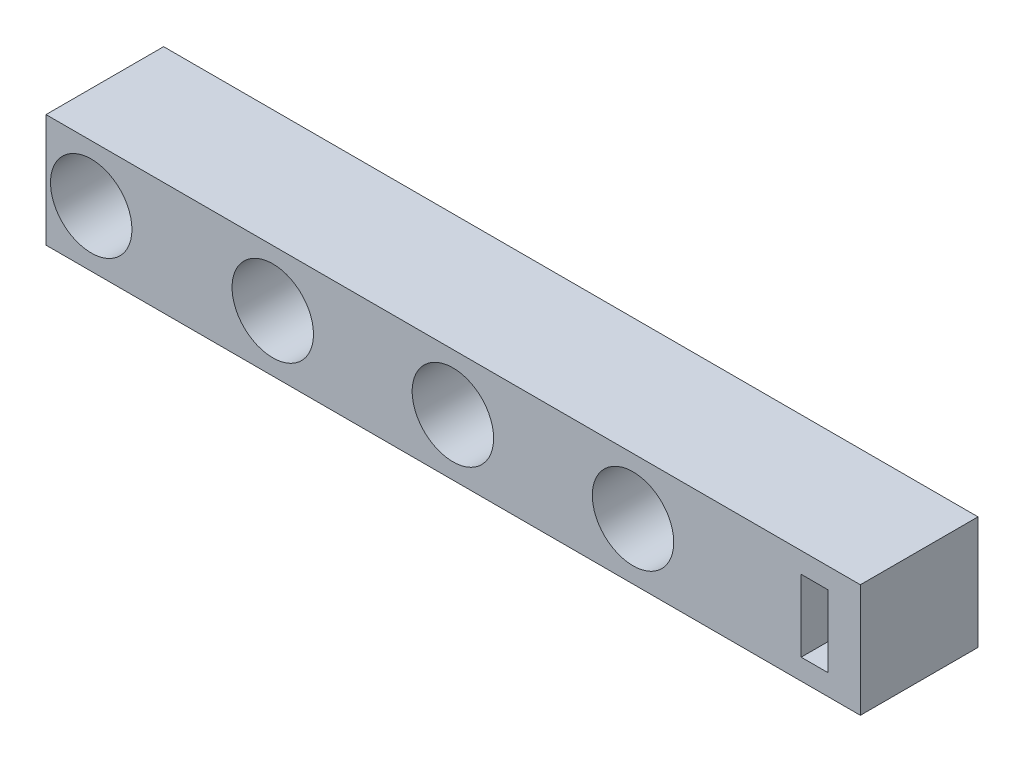
SolidWorks part; units mm, degrees
ref_plane "Ebene vorne" through (0, 0, 0) normal (0, 0, 1) x (1, 0, 0)
ref_plane "Ebene oben" through (0, 0, 0) normal (0, 1, 0) x (1, 0, 0)
ref_plane "Ebene rechts" through (0, 0, 0) normal (1, 0, 0) x (0, 0, -1)
sketch "Skizze1" plane through (0, 0, 0) normal (0, 0, 1) x (1, 0, 0)
  line L0 (20, 32.4365) -> (20, -11.0179) construction
  line L1 (0, 0) -> (180, 0)
  line L2 (0, 0) -> (0, 25)
  line L3 (0, 25) -> (180, 25)
  line L4 (180, 0) -> (180, 25)
  line L5 (40, 32.4365) -> (40, -11.0179) construction
  line L6 (60, 32.4365) -> (60, -11.0179) construction
  line L7 (80, 32.4365) -> (80, -11.0179) construction
  line L8 (100, 32.4365) -> (100, -11.0179) construction
  line L9 (120, 32.4365) -> (120, -11.0179) construction
  line L10 (140, 32.4365) -> (140, -11.0179) construction
  line L11 (160, 32.4365) -> (160, -11.0179) construction
  dimension "D1" = 180
  dimension "D2" = 25
  dimension "D3" = 20
  dimension "D4" = 20
  dimension "D5" = 20
  dimension "D6" = 20
  dimension "D7" = 20
  dimension "D8" = 20
  dimension "D9" = 20
  dimension "D10" = 20
extrude "Aufsatz-Linear austragen1" add sketch "Skizze1" along normal blind 26
sketch "Skizze6" plane through (0, 0, 26) normal (0, 0, 1) x (1, 0, 0)
  line L0 (20, 30.7651) -> (20, -8.869)
  line L1 (40, 30.7651) -> (40, -11.0179)
  line L2 (60, 30.7651) -> (60, -11.0179)
  line L3 (80, 30.7651) -> (80, -11.0179)
  line L4 (100, 30.7651) -> (100, -8.869)
  line L5 (120, 30.7651) -> (120, -11.0179)
  line L6 (140, 30.7651) -> (140, -12.928)
  line L7 (160, 30.7651) -> (160, -11.0179)
  line L8 (0, 25) -> (0, 0) construction
  point P18 (20, 10.9481)
  dimension "D1" = 20
  dimension "D2" = 20
  dimension "D3" = 20
  dimension "D4" = 20
  dimension "D5" = 20
  dimension "D6" = 20
  dimension "D7" = 20
  dimension "D8" = 20
hole_wizard "Ø18.0 (18) Durchmesser Bohrung2" positions "Skizze7" profile "Skizze8" hole size "Ø18.0" standard "DIN" end condition through all
sketch "Skizze7" plane through (0, 0, 26) normal (0, 0, 1) x (1, 0, 0)
  point P0 (9.9956, 12.5)
  point P2 (50.1213, 12.5)
  point P4 (89.9347, 12.5)
  point P6 (129.7481, 12.5)
sketch "Skizze8" plane through (9.9956, 12.5, 26) normal (1, 0, 0) x (0, -1, 0)
  line L0 (0, 0) -> (0, 26)
  line L1 (0, 26) -> (9, 26)
  line L2 (9, 26) -> (9, 0)
  line L5 (9, 0) -> (0, 0)
  line L11 (0, -6.35) -> (0, 107.95) construction
  dimension "Bohrerdurchmesser" = 18
  dimension "Bohrungstiefe" = 26
sketch "Skizze9" plane through (0, 0, 26) normal (0, 0, 1) x (1, 0, 0)
  line L1 (172.8107, 20.4583) -> (166.9131, 20.4583)
  line L2 (172.8107, 20.4583) -> (172.8107, 4.591)
  line L3 (172.8107, 4.591) -> (166.9131, 4.591)
  line L4 (166.9131, 20.4583) -> (166.9131, 4.591)
  dimension "D1" = 15.8673
  dimension "D2" = 5.8976
extrude "Schnitt-Linear austragen1" cut sketch "Skizze9" against normal through all
